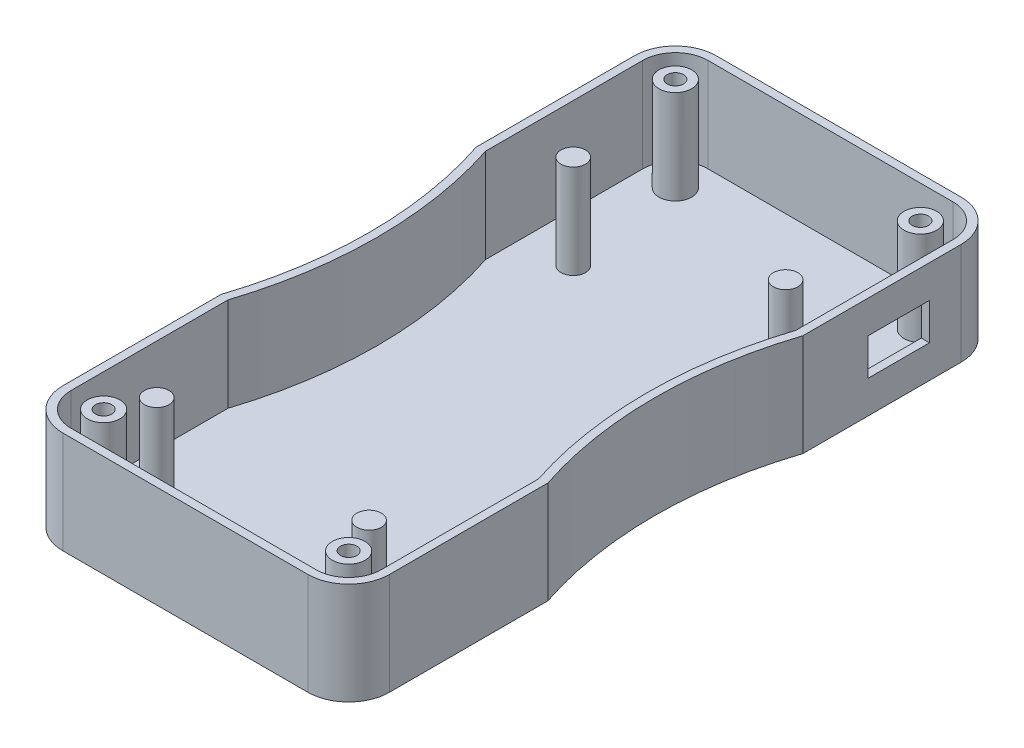
SolidWorks part; units mm, degrees
ref_plane "Front Plane" through (0, 0, 0) normal (0, 0, 1) x (1, 0, 0)
ref_plane "Top Plane" through (0, 0, 0) normal (0, 1, 0) x (1, 0, 0)
ref_plane "Right Plane" through (0, 0, 0) normal (1, 0, 0) x (0, 0, -1)
sketch "Sketch1" plane through (0, 0, 0) normal (0, 1, 0) x (1, 0, 0)
  line L1 (0, 0) -> (80, 0)
  line L2 (0, 0) -> (0, 160)
  line L3 (0, 160) -> (80, 160)
  line L4 (80, 0) -> (80, 160)
  dimension "D1" = 80
  dimension "D2" = 160
extrude "Boss-Extrude1" add sketch "Sketch1" against normal blind 25
sketch "Sketch2" plane through (0, 0, 0) normal (0, 1, 0) x (1, 0, 0)
  line L0 (40, 160) -> (40, 0) construction
  line L1 (80, 160) -> (0, 160) construction
  line L2 (0, 0) -> (80, 0) construction
  line L6 (80, 0) -> (80, 160) construction
  circle A0 centre (-95, 80) radius 100
  circle A1 centre (175, 80) radius 100
  dimension "D2" = 200
  dimension "D1" = 95
  dimension "D3" = 80
extrude "Cut-Extrude1" cut sketch "Sketch2" against normal through all
fillet "Fillet1" radius 10 4 edges at (0, -12.5, -160) (80, -12.5, -160) (0, -12.5, 0) (80, -12.5, 0)
shell "Shell1" thickness 2
sketch "Sketch3" plane through (0, -23, 0) normal (0, 1, 0) x (1, 0, 0)
  line L0 (70, 160) -> (10, 160) construction
  line L1 (0, 150) -> (0, 111.225) construction
  line L2 (40, 158) -> (40, 2) construction
  line L3 (70, 158) -> (10, 158) construction
  line L4 (10, 2) -> (70, 2) construction
  line L5 (7, 80) -> (73, 80) construction
  circle A0 centre (10, 150) radius 4
  arc A2 (2, 48.4564) -> (2, 111.5436) centre (-95, 80) ccw construction
  arc A3 (78, 111.5436) -> (78, 48.4564) centre (175, 80) ccw construction
  circle A4 centre (70, 150) radius 4
  circle A5 centre (70, 10) radius 4
  circle A6 centre (10, 10) radius 4
  dimension "D3" = 8
  dimension "D1" = 10
  dimension "D2" = 10
extrude "Boss-Extrude2" add sketch "Sketch3" along normal through all
sketch "Sketch6" plane through (0, 0, 0) normal (0, 1, 0) x (1, 0, 0)
  line L0 (40, 158) -> (40, 2) construction
  line L1 (70, 158) -> (10, 158) construction
  line L2 (10, 2) -> (70, 2) construction
  line L3 (7, 80) -> (75, 80) construction
  circle A0 centre (10, 150) radius 2
  arc A3 (2, 48.4564) -> (2, 111.5436) centre (-95, 80) ccw construction
  arc A4 (80, 111.225) -> (80, 48.775) centre (175, 80) ccw construction
  circle A5 centre (70, 150) radius 2
  circle A6 centre (70, 10) radius 2
  circle A7 centre (10, 10) radius 2
  dimension "D1" = 4
extrude "Cut-Extrude2" cut sketch "Sketch6" against normal blind 10
sketch "Sketch7" plane through (0, -23, 0) normal (0, 1, 0) x (1, 0, 0)
  line L0 (10, 15) -> (70, 15) construction
  line L1 (70, 15) -> (70, 125) construction
  line L2 (70, 125) -> (10, 125) construction
  line L3 (10, 125) -> (10, 15) construction
  line L4 (0, 48.775) -> (0, 10) construction
  line L5 (10, 0) -> (70, 0) construction
  line L6 (40, 125) -> (40, 15) construction
  line L7 (10, 70) -> (70, 70) construction
  circle A0 centre (14, 121) radius 3
  circle A1 centre (66, 121) radius 3
  circle A2 centre (14, 19) radius 3
  circle A3 centre (66, 19) radius 3
  point P6 (0, 29.3875)
  dimension "D5" = 6
  dimension "D1" = 60
  dimension "D2" = 10
  dimension "D3" = 15
  dimension "D4" = 110
  dimension "D6" = 4
  dimension "D7" = 4
extrude "Boss-Extrude3" add sketch "Sketch7" along normal through all
sketch "Sketch8" plane through (80, 0, 0) normal (1, 0, 0) x (0, 0, -1)
  line L1 (142.225, -8) -> (127.225, -8)
  line L2 (142.225, -8) -> (142.225, -17)
  line L3 (142.225, -17) -> (127.225, -17)
  line L4 (127.225, -8) -> (127.225, -17)
  line L8 (111.225, -25) -> (150, -25) construction
  line L9 (111.225, -25) -> (111.225, 0) construction
  point P10 (142.225, -12.5)
  dimension "D1" = 9
  dimension "D2" = 15
  dimension "D3" = 12.5
  dimension "D4" = 16
extrude "Cut-Extrude3" cut sketch "Sketch8" against normal blind 10
